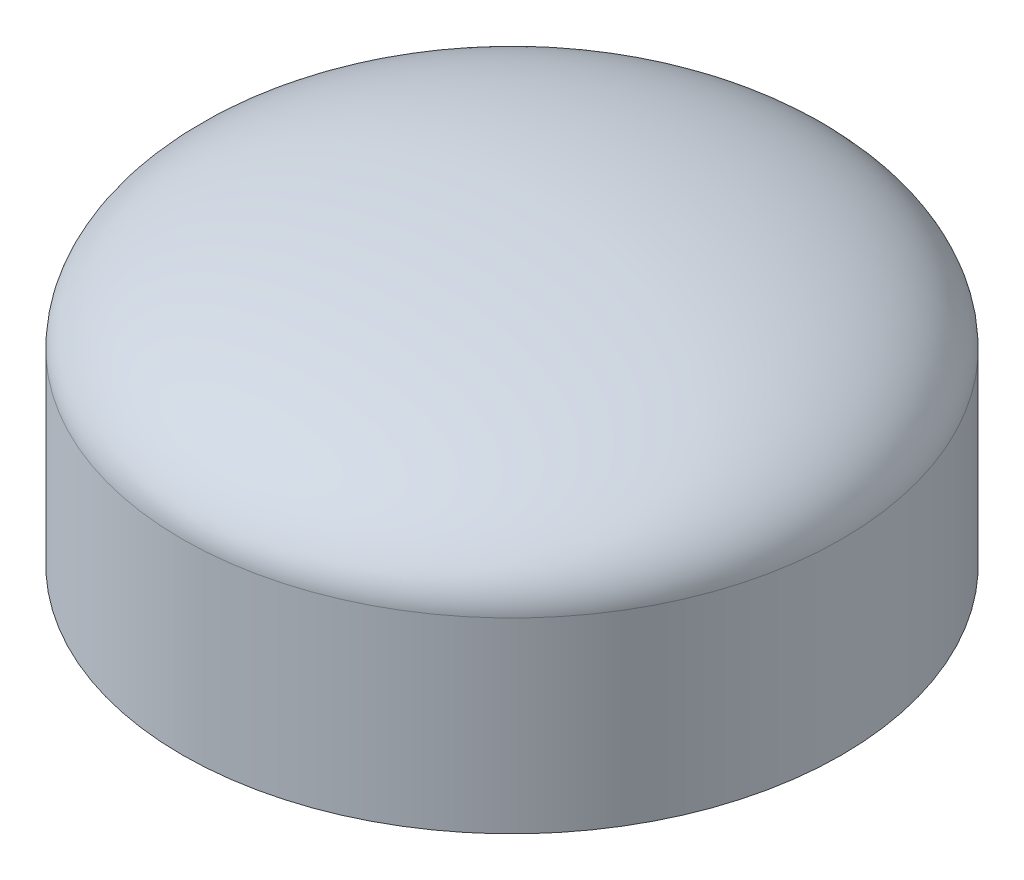
SolidWorks part; units mm, degrees
ref_plane "Front Plane" through (0, 0, 0) normal (0, 0, 1) x (1, 0, 0)
ref_plane "Top Plane" through (0, 0, 0) normal (0, 1, 0) x (1, 0, 0)
ref_plane "Right Plane" through (0, 0, 0) normal (1, 0, 0) x (0, 0, -1)
sketch "Sketch1" plane through (0, 0, 0) normal (0, 0, 1) x (1, 0, 0)
  line L0 (0, 0) -> (41.1, 0) construction
  line L1 (41.1, 0) -> (41.1, 25)
  line L2 (0, 0) -> (0, 69.4201) construction
  line L3 (41.1, 0) -> (44.1, 0)
  line L4 (44.1, 0) -> (44.1, 25)
  line L5 (41.1, 25) -> (0, 25) construction
  line L6 (0, 38) -> (0, 41)
  ellipse E0 centre (0, 25) end of major axis (44.1, 25) minor radius 16 (0, 41) -> (44.1, 25) cw
  ellipse E1 centre (0, 25) end of major axis (41.1, 25) minor radius 13 (0, 38) -> (41.1, 25) cw
  point P3 (44.1, 12.5)
  dimension "D1" = 41.1
  dimension "D2" = 3
  dimension "D3" = 25
  dimension "D4" = 25
  dimension "D5" = 16
  dimension "D6" = 3
revolve "Revolve1" add sketch "Sketch1" angle 360 about L6
